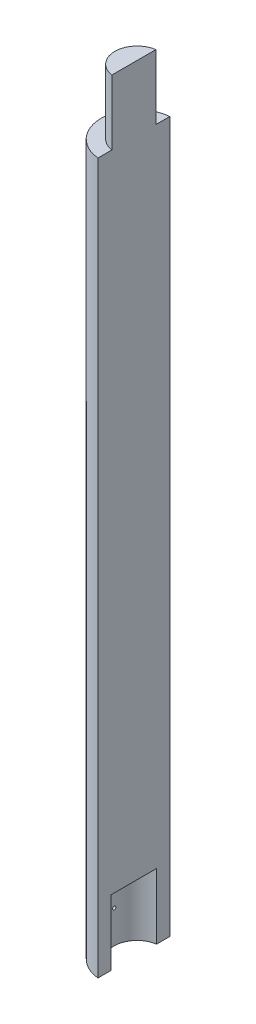
SolidWorks part; units mm, degrees
ref_plane "Front Plane" through (0, 0, 0) normal (0, 0, 1) x (1, 0, 0)
ref_plane "Top Plane" through (0, 0, 0) normal (0, 1, 0) x (1, 0, 0)
ref_plane "Right Plane" through (0, 0, 0) normal (1, 0, 0) x (0, 0, -1)
sketch "Sketch1" plane through (0, 0, 0) normal (0, 1, 0) x (1, 0, 0)
  line L0 (0, 11) -> (0, -11)
  arc A0 (0, 11) -> (0, -11) centre (0, 0) ccw
extrude "Boss-Extrude1" add sketch "Sketch1" along normal blind 216.6667 contours A0 L0
sketch "Sketch2" plane through (0, 0, 0) normal (0, 1, 0) x (1, 0, 0)
  line L0 (0, 6.8) -> (0, -6.8)
  arc A0 (0, 6.8) -> (0, -6.8) centre (0, 0) ccw
extrude "Boss-Extrude2" add sketch "Sketch2" along normal blind 19.8 from offset 216.6667
sketch "Sketch4" plane through (0, 0, 0) normal (1, 0, 0) x (0, 0, -1)
  line L2 (0, 12.1) -> (0, -12.1) construction
  circle A0 centre (0, 226.6667) radius 0.5
extrude "Cut-Extrude2" cut sketch "Sketch4" against normal blind 9 from offset 1.4 offset against normal yes
sketch "Sketch6" plane through (0, 0, 0) normal (0, 1, 0) x (1, 0, 0)
  circle A0 centre (0, 0) radius 7
extrude "Cut-Extrude3" cut sketch "Sketch6" along normal blind 20
sketch "Sketch7" plane through (0, 0, 0) normal (1, 0, 0) x (0, 0, -1)
  line L1 (0, 12.1) -> (0, -12.1) construction
  circle A0 centre (0, 10) radius 0.5
extrude "Cut-Extrude4" cut sketch "Sketch7" against normal blind 20 and the other way through all
sketch "Sketch10" plane through (0, 0, 0) normal (0, 0, 1) x (1, 0, 0)
  line L1 (0, -12.1) -> (0, 12.1) construction
  circle A0 centre (0, 5) radius 0.5
extrude "Cut-Extrude5" cut sketch "Sketch10" against normal through all both and the other way through all
sketch "Sketch11" plane through (0, 0, 0) normal (0, 0, 1) x (1, 0, 0)
  line L0 (6.0656, 0) -> (-6.0656, 0) construction
  line L7 (0, 216.6667) -> (-11, 216.6667) construction
  line L9 (-0.9997, 216.6667) -> (2.5003, 216.6667)
  line L10 (-0.9997, 216.6667) -> (-0.9997, 0)
  line L11 (2.5003, 216.6667) -> (2.5003, 0)
  line L12 (-0.9997, 0) -> (2.5003, 0)
extrude "Cut-Extrude6" cut sketch "Sketch11" against normal through all both and the other way through all
sketch "Sketch12" plane through (0, 0, 0) normal (0, 0, 1) x (1, 0, 0)
  line L0 (-0.9997, 216.6667) -> (2.4997, 216.6667)
  line L1 (-0.9997, 216.6667) -> (-0.9997, 236.6667)
  line L2 (2.4997, 216.6667) -> (2.4997, 236.6667)
  line L3 (-0.9997, 236.6667) -> (2.4997, 236.6667)
extrude "Cut-Extrude7" cut sketch "Sketch12" against normal through all both and the other way through all
equation "\"V\"=0"
